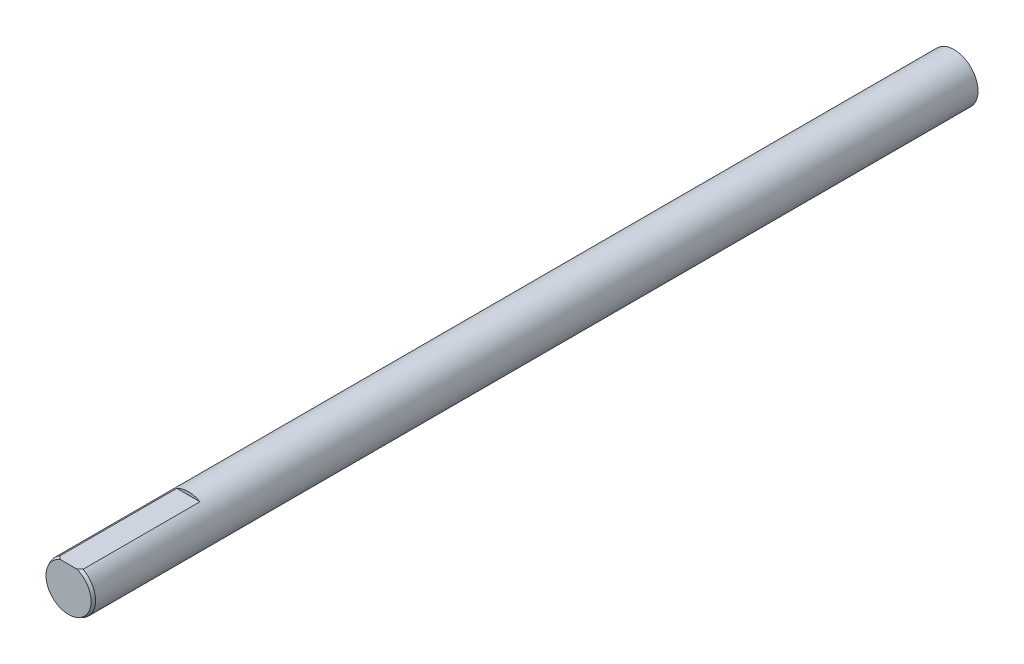
SolidWorks part; units mm, degrees
material "1.0038 (S235JRG2)"
ref_plane "Horní rovina" through (0, 0, 0) normal (0, 0, 1) x (1, 0, 0)
ref_plane "Přední rovina" through (0, 0, 0) normal (0, 1, 0) x (1, 0, 0)
ref_plane "Pravá rovina" through (0, 0, 0) normal (1, 0, 0) x (0, 0, -1)
sketch "Skica1" plane through (0, 0, 0) normal (0, 0, 1) x (1, 0, 0)
  circle A0 centre (0, 0) radius 4
  dimension "D1" = 8
extrude "Přidat vysunutím1" add sketch "Skica1" along normal blind 148
chamfer "Zkosení1" distance 0.5 angle 25 2 edges at (4, 0, 0) (4, 0, 148)
sketch "Skica2" plane through (0, 0, 148) normal (0, 0, 1) x (1, 0, 0)
  line L0 (-1.9365, 3.5) -> (1.9365, 3.5)
  circle A0 centre (0, 0) radius 4 construction
  arc A1 (1.9365, 3.5) -> (-1.9365, 3.5) centre (0, 0) ccw
  dimension "D1" = 3.5
extrude "Odebrat vysunutím1" cut sketch "Skica2" against normal blind 20
